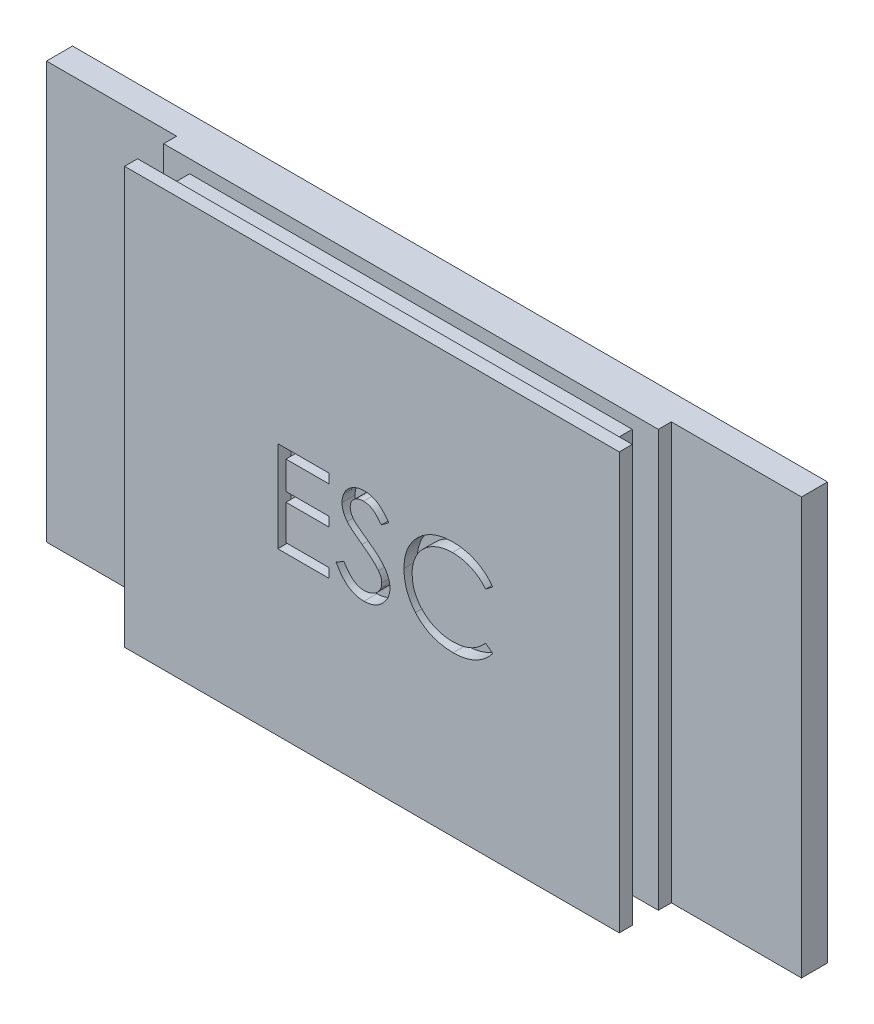
SolidWorks part; units mm, degrees
ref_plane "Front Plane" through (0, 0, 0) normal (0, 0, 1) x (1, 0, 0)
ref_plane "Top Plane" through (0, 0, 0) normal (0, 1, 0) x (1, 0, 0)
ref_plane "Right Plane" through (0, 0, 0) normal (1, 0, 0) x (0, 0, -1)
sketch "Sketch1" plane through (0, 0, 0) normal (0, 0, 1) x (1, 0, 0)
  line L1 (-14.5, 8) -> (14.5, 8)
  line L2 (-14.5, 8) -> (-14.5, -8)
  line L3 (-14.5, -8) -> (14.5, -8)
  line L4 (14.5, 8) -> (14.5, -8)
  point P0 (0, 0)
  dimension "D1" = 29
  dimension "D2" = 16
extrude "Boss-Extrude2" add sketch "Sketch1" along normal blind 1 contours L1 L4 L3 L2
sketch "Sketch3" plane through (0, 0, 1) normal (0, 0, 1) x (1, 0, 0)
  line L0 (-14.5, 8) -> (14.5, 8) construction
  line L1 (-9.5, 8) -> (9.5, 8)
  line L2 (-9.5, 8) -> (-9.5, -8)
  line L3 (-9.5, -8) -> (9.5, -8)
  line L4 (9.5, 8) -> (9.5, -8)
  line L5 (-14.5, -8) -> (14.5, -8) construction
  line L6 (-14.5, 8) -> (-14.5, -8) construction
  line L7 (14.5, 8) -> (14.5, -8) construction
  dimension "D1" = 5
  dimension "D2" = 5
extrude "Boss-Extrude3" add sketch "Sketch3" along normal blind 2
sketch "Sketch5" plane through (-9.5, 0, 0) normal (-1, 0, 0) x (0, 0, 1)
  line L0 (3, 8) -> (1, 8) construction
  line L1 (2.5, 8) -> (1.5, 8)
  line L2 (2.5, 8) -> (2.5, -8)
  line L3 (2.5, -8) -> (1.5, -8)
  line L4 (1.5, 8) -> (1.5, -8)
  line L5 (3, -8) -> (1, -8) construction
  line L6 (3, 8) -> (3, -8) construction
  line L7 (1, 8) -> (1, -8) construction
  dimension "D1" = 0.5
  dimension "D2" = 0.5
extrude "Cut-Extrude1" cut sketch "Sketch5" against normal blind 1 contours L2 L3 L4 L1
sketch "Sketch7" plane through (9.5, 0, 0) normal (1, 0, 0) x (0, 0, -1)
  line L0 (-3, 8) -> (-1, 8) construction
  line L1 (-1.5, 8) -> (-2.5, 8)
  line L2 (-1.5, 8) -> (-1.5, -8)
  line L3 (-1.5, -8) -> (-2.5, -8)
  line L4 (-2.5, 8) -> (-2.5, -8)
  line L5 (-3, -8) -> (-1, -8) construction
  line L6 (-3, -8) -> (-3, 8) construction
  line L7 (-1, 8) -> (-1, -8) construction
  dimension "D1" = 0.5
  dimension "D2" = 0.5
extrude "Cut-Extrude2" cut sketch "Sketch7" against normal blind 1
sketch "Sketch8" plane through (0, -8, 0) normal (0, -1, 0) x (1, 0, 0)
  line L1 (-8.5, 2.5) -> (8.5, 2.5)
  line L2 (-8.5, 2.5) -> (-8.5, 1.5)
  line L3 (-8.5, 1.5) -> (8.5, 1.5)
  line L4 (8.5, 2.5) -> (8.5, 1.5)
extrude "Cut-Extrude3" cut sketch "Sketch8" against normal blind 0.5
sketch "Sketch9" plane through (0, 8, 0) normal (0, 1, 0) x (1, 0, 0)
  line L1 (-8.5, -1.5) -> (8.5, -1.5)
  line L2 (-8.5, -1.5) -> (-8.5, -2.5)
  line L3 (-8.5, -2.5) -> (8.5, -2.5)
  line L4 (8.5, -1.5) -> (8.5, -2.5)
extrude "Cut-Extrude4" cut sketch "Sketch9" against normal blind 0.5
sketch "Sketch10" plane through (0, 0, 3) normal (0, 0, 1) x (1, 0, 0)
  text T0 "ESC"
extrude "Cut-Extrude5" cut sketch "Sketch10" against normal blind 0.5
